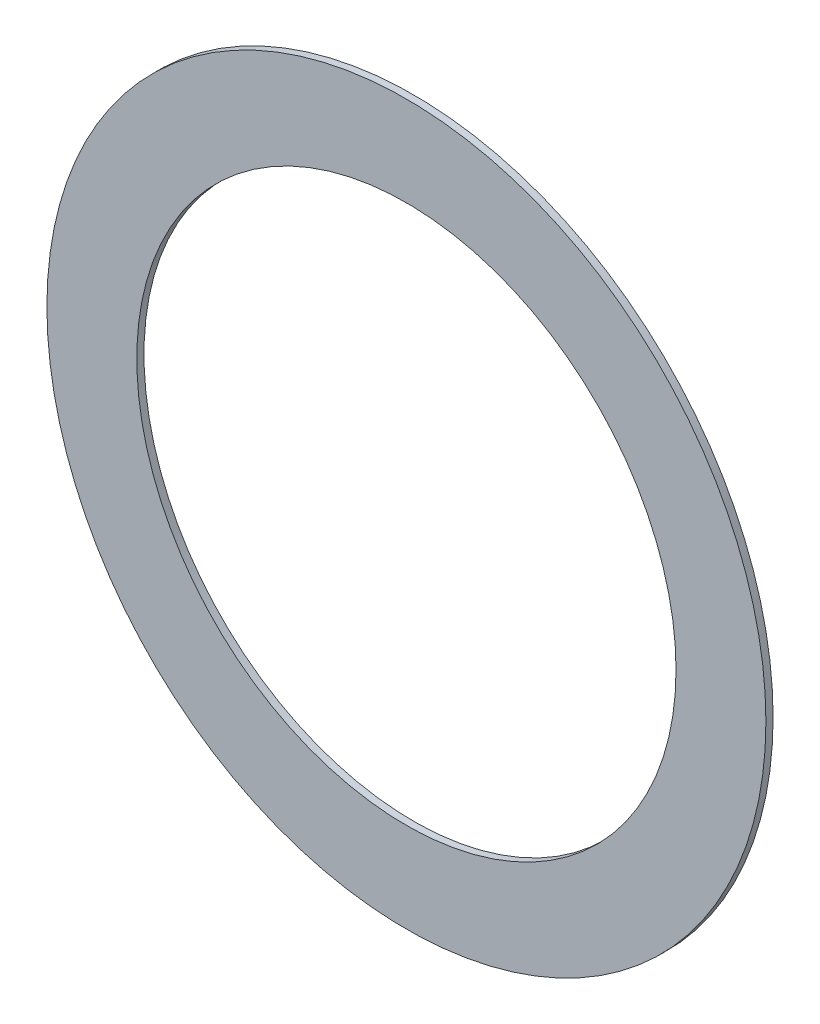
SolidWorks part; units mm, degrees
ref_plane "Front Plane" through (0, 0, 0) normal (0, 0, 1) x (1, 0, 0)
ref_plane "Top Plane" through (0, 0, 0) normal (0, 1, 0) x (1, 0, 0)
ref_plane "Right Plane" through (0, 0, 0) normal (1, 0, 0) x (0, 0, -1)
sketch "Sketch1" plane through (0, 0, 0) normal (0, 0, 1) x (1, 0, 0)
  circle A0 centre (0, 0) radius 37.5
  circle A1 centre (0, 0) radius 50
  dimension "D1" = 75
  dimension "D2" = 100
extrude "Boss-Extrude1" add sketch "Sketch1" along normal blind 1
